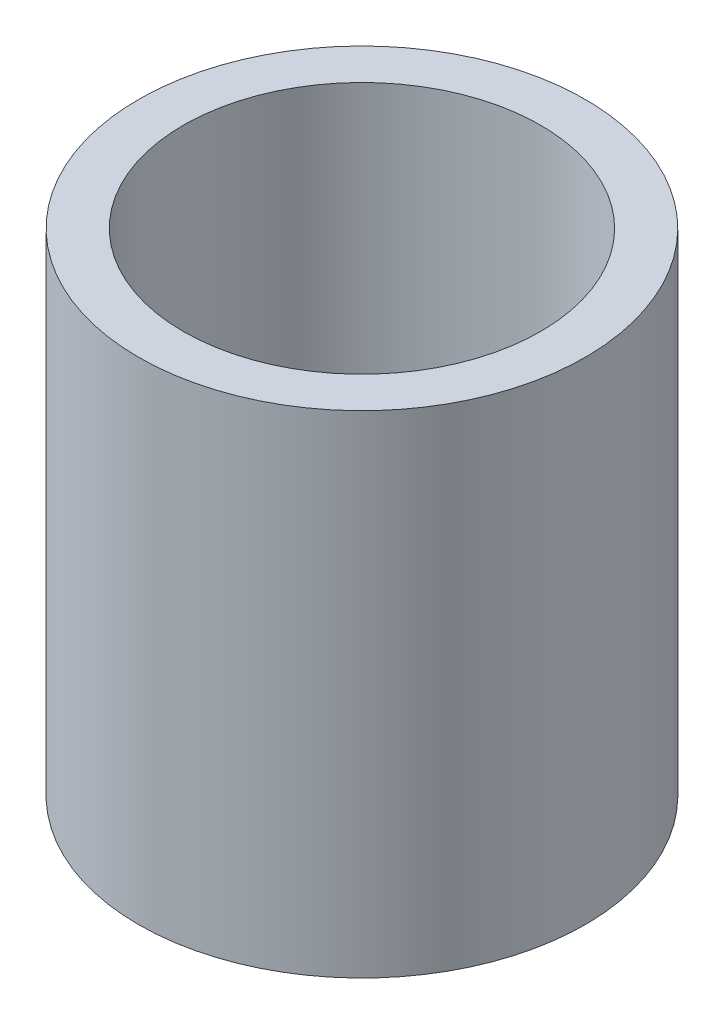
SolidWorks part; units mm, degrees
ref_plane "Front Plane" through (0, 0, 0) normal (0, 0, 1) x (1, 0, 0)
ref_plane "Top Plane" through (0, 0, 0) normal (0, 1, 0) x (1, 0, 0)
ref_plane "Right Plane" through (0, 0, 0) normal (1, 0, 0) x (0, 0, -1)
sketch "Sketch1" plane through (0, 0, 0) normal (0, 1, 0) x (1, 0, 0)
  circle A0 centre (0, 0) radius 0.625
  circle A1 centre (0, 0) radius 0.5
  dimension "D1" = 1.25
  dimension "D2" = 1
extrude "Boss-Extrude1" add sketch "Sketch1" along normal blind 1.375
